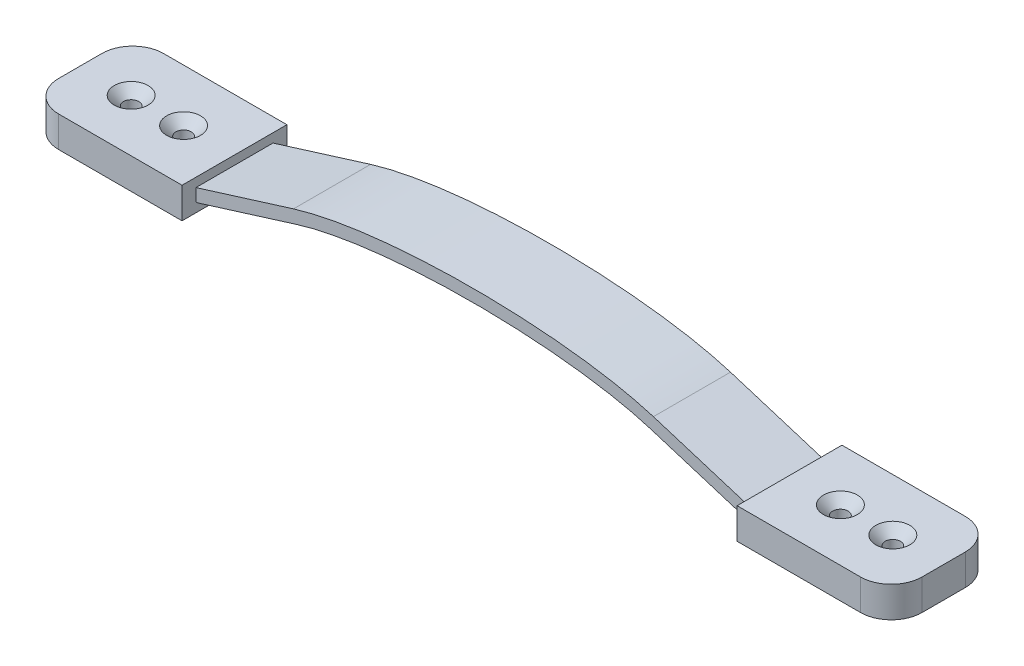
SolidWorks part; units mm, degrees
ref_plane "Front Plane" through (0, 0, 0) normal (0, 0, 1) x (1, 0, 0)
ref_plane "Top Plane" through (0, 0, 0) normal (0, 1, 0) x (1, 0, 0)
ref_plane "Right Plane" through (0, 0, 0) normal (1, 0, 0) x (0, 0, -1)
sketch "Sketch1" plane through (0, 0, 0) normal (0, 1, 0) x (1, 0, 0)
  line L1 (0, 0) -> (50, 0)
  line L2 (0, 0) -> (0, 34)
  line L3 (0, 34) -> (50, 34)
  line L4 (50, 0) -> (50, 34)
  line L5 (230, 34) -> (280, 34)
  line L6 (230, 34) -> (230, 0)
  line L7 (230, 0) -> (280, 0)
  line L8 (280, 34) -> (280, 0)
  dimension "D1" = 34
  dimension "D2" = 50
  dimension "D3" = 50
  dimension "D4" = 34
  dimension "D5" = 180
extrude "Boss-Extrude1" add sketch "Sketch1" along normal blind 10
fillet "Fillet1" radius 10 2 edges at (0, 5, -34) (0, 5, 0)
fillet "Fillet2" radius 10 2 edges at (280, 5, -34) (280, 5, 0)
ref_plane "Plane1" through (0, 0, -17) normal (0, 0, 1) x (1, 0, 0)
sketch "Sketch3" plane through (0, 0, -17) normal (0, 0, 1) x (1, 0, 0)
  line L0 (198.3567, 16.9319) -> (230, 7.0944)
  line L1 (197.7629, 15.022) -> (230, 5) construction
  line L2 (50, 5) -> (82.2371, 15.022) construction
  line L3 (50, 7.0944) -> (81.6433, 16.9319)
  line L4 (50, 10) -> (10, 10)
  line L5 (10, 10) -> (10, 0)
  line L6 (10, 0) -> (50, 0)
  line L7 (50, 0) -> (50, 10)
  line L8 (50, 10) -> (10, 10)
  line L9 (10, 10) -> (10, 0)
  line L10 (10, 0) -> (50, 0)
  line L11 (50, 0) -> (50, 10)
  line L12 (230, 0) -> (270, 0)
  line L13 (270, 0) -> (270, 10)
  line L14 (270, 10) -> (230, 10)
  line L15 (230, 10) -> (230, 0)
  line L16 (230, 0) -> (270, 0)
  line L17 (270, 0) -> (270, 10)
  line L18 (270, 10) -> (230, 10)
  line L19 (230, 10) -> (230, 0)
  line L20 (197.1692, 13.1122) -> (229.4063, 3.0902)
  line L21 (50.5937, 3.0902) -> (82.8308, 13.1122)
  line L22 (50.5937, 3.0902) -> (82.8308, 13.1122) construction
  line L23 (49.4063, 6.9098) -> (81.6433, 16.9319) construction
  line L24 (50.5937, 3.0902) -> (50, 3.0902)
  line L25 (229.4063, 3.0902) -> (230, 3.0902)
  line L26 (198.3567, 16.9319) -> (230.5937, 6.9098) construction
  line L27 (50, 7.0944) -> (50, 3.0902)
  line L28 (230, 7.0944) -> (230, 3.0902)
  ellipse E0 centre (140, 5) end of major axis (212.1018, 5) minor radius 16.7455 (197.7629, 15.022) -> (82.2371, 15.022) ccw construction
  spline S0 degree 1 poles (198.3567, 16.9319) (81.6433, 16.9319) knots 0 0 1 1 construction
  spline S1 degree 3 poles (198.3567, 16.9319) (197.9215, 17.0672) (197.0583, 17.3274) (195.247, 17.8423) (192.8789, 18.4583) (189.8623, 19.1569) (185.6251, 20.0303) (179.9467, 21.0096) (172.6085, 21.9914) (164.8408, 22.7679) (154.0469, 23.5171) (140, 23.8978) (125.9531, 23.5171) (115.1592, 22.7679) (107.3915, 21.9914) (100.0533, 21.0096) (94.3749, 20.0303) (90.1377, 19.1569) (87.1211, 18.4583) (84.753, 17.8423) (82.9417, 17.3274) (82.0785, 17.0672) (81.6433, 16.9319) knots 0.641614 0.641614 0.641614 0.641614 0.670651 0.699688 0.757762 0.815836 0.87391 0.990057 1.106205 1.222353 1.338501 1.570796 1.803092 1.91924 2.035387 2.151535 2.267683 2.325757 2.383831 2.441905 2.470942 2.499979 2.499979 2.499979 2.499979
  spline S2 degree 1 poles (197.1692, 13.1122) (82.8308, 13.1122) knots 0 0 1 1 construction
  spline S3 degree 3 poles (197.1692, 13.1122) (196.7552, 13.2409) (195.9354, 13.4881) (194.2035, 13.9804) (191.9272, 14.5726) (189.0098, 15.2484) (184.8932, 16.0971) (179.3474, 17.0539) (172.1484, 18.0172) (164.5061, 18.7813) (153.8671, 19.5199) (140, 19.896) (126.1329, 19.5199) (115.4939, 18.7813) (107.8516, 18.0172) (100.6526, 17.0539) (95.1068, 16.0971) (90.9902, 15.2484) (88.0728, 14.5726) (85.7965, 13.9804) (84.0646, 13.4881) (83.2448, 13.2409) (82.8308, 13.1122) knots 0.641614 0.641614 0.641614 0.641614 0.670651 0.699688 0.757762 0.815836 0.87391 0.990057 1.106205 1.222353 1.338501 1.570796 1.803092 1.91924 2.035387 2.151535 2.267683 2.325757 2.383831 2.441905 2.470942 2.499979 2.499979 2.499979 2.499979
  dimension "D3" = 2
  dimension "D1" = 0
  dimension "D2" = 0
  dimension "D4" = 2
extrude "Boss-Extrude2" add sketch "Sketch3" along normal mid plane 25 contours S3 L20 L25 L19 L0 S1 L3 L11 L24 L21
sketch "Sketch4" plane through (0, 10, 0) normal (0, 1, 0) x (1, 0, 0)
  line L0 (0, 17) -> (280, 17) construction
  line L1 (140, 17) -> (140, 29.5) construction
  line L2 (198.3567, 29.5) -> (81.6433, 29.5) construction
  line L4 (50, 34) -> (10, 34)
  line L5 (0, 24) -> (0, 10)
  line L6 (10, 0) -> (50, 0)
  line L7 (50, 0) -> (50, 34)
  line L8 (50, 34) -> (10, 34)
  line L9 (0, 24) -> (0, 10)
  line L10 (10, 0) -> (50, 0)
  line L11 (50, 0) -> (50, 34)
  line L12 (280, 10) -> (280, 24)
  line L13 (270, 34) -> (230, 34)
  line L14 (230, 34) -> (230, 0)
  line L15 (230, 0) -> (270, 0)
  line L16 (280, 10) -> (280, 24)
  line L17 (270, 34) -> (230, 34)
  line L18 (230, 34) -> (230, 0)
  line L19 (230, 0) -> (270, 0)
  circle A0 centre (16.5, 17) radius 2.5
  circle A1 centre (33.5, 17) radius 2.5
  arc A2 (10, 34) -> (0, 24) centre (10, 24) ccw
  arc A3 (0, 10) -> (10, 0) centre (10, 10) ccw
  arc A4 (10, 34) -> (0, 24) centre (10, 24) ccw
  arc A5 (0, 10) -> (10, 0) centre (10, 10) ccw
  arc A6 (280, 24) -> (270, 34) centre (270, 24) ccw
  arc A7 (270, 0) -> (280, 10) centre (270, 10) ccw
  arc A8 (280, 24) -> (270, 34) centre (270, 24) ccw
  arc A9 (270, 0) -> (280, 10) centre (270, 10) ccw
  circle A10 centre (263.5, 17) radius 2.5
  circle A11 centre (246.5, 17) radius 2.5
  dimension "D3" = 5
  dimension "D4" = 16.5
  dimension "D5" = 16.5
  dimension "D1" = 0
  dimension "D2" = 0
extrude "Cut-Extrude1" cut sketch "Sketch4" against normal through all contours A0 | A1 | A11 | A10
chamfer "Chamfer1" distance 3 angle 45 4 edges at (263.5, 10, -14.5) (246.5, 10, -14.5) (33.5, 10, -14.5) (16.5, 10, -14.5)
